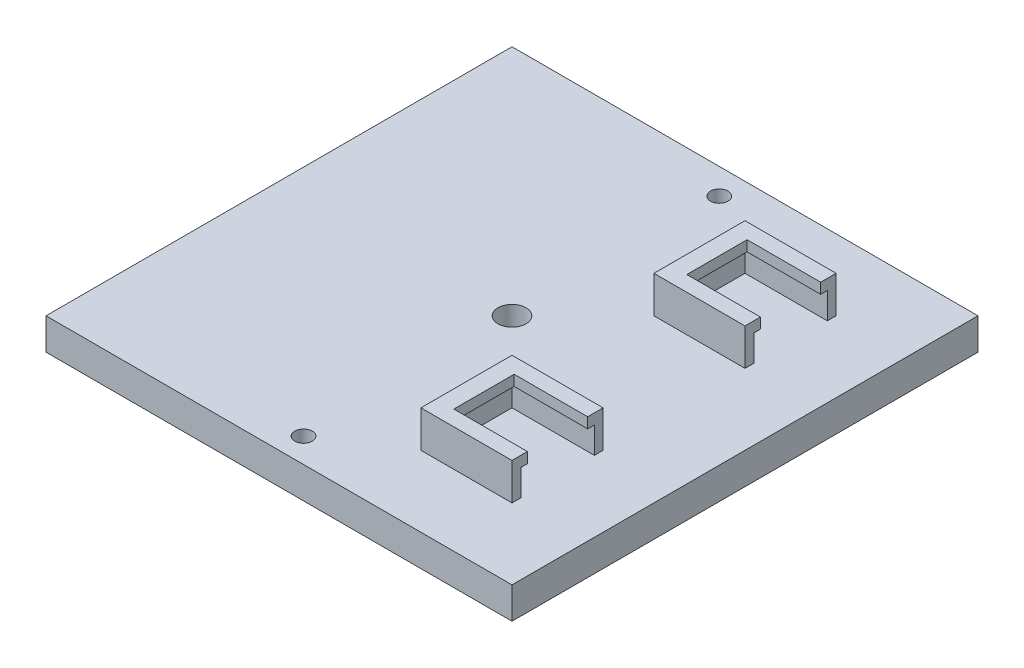
SolidWorks part; units mm, degrees
ref_plane "Front Plane" through (0, 0, 0) normal (0, 0, 1) x (1, 0, 0)
ref_plane "Top Plane" through (0, 0, 0) normal (0, 1, 0) x (1, 0, 0)
ref_plane "Right Plane" through (0, 0, 0) normal (1, 0, 0) x (0, 0, -1)
sketch "Sketch1" plane through (0, 0, 0) normal (0, 1, 0) x (1, 0, 0)
  line L1 (-66.5, -66.5) -> (66.5, -66.5)
  line L2 (-66.5, -66.5) -> (-66.5, 66.5)
  line L3 (-66.5, 66.5) -> (66.5, 66.5)
  line L4 (66.5, -66.5) -> (66.5, 66.5)
  line L5 (-66.5, -66.5) -> (66.5, 66.5) construction
  line L6 (-66.5, 66.5) -> (66.5, -66.5) construction
  point P0 (0, 0)
extrude "Boss-Extrude2" add sketch "Sketch1" along normal blind 136
sketch "Sketch2" plane through (0, 0, 66.5) normal (0, 0, 1) x (1, 0, 0)
  line L0 (66.5, 136) -> (66.5, 0) construction
  line L1 (-66.5, 136) -> (66.5, 136)
  line L2 (-66.5, 136) -> (-66.5, 127)
  line L3 (-66.5, 127) -> (66.5, 127)
  line L4 (66.5, 136) -> (66.5, 127)
  line L6 (-66.5, 0) -> (66.5, 0)
  line L7 (-66.5, 0) -> (-66.5, 9)
  line L8 (-66.5, 9) -> (66.5, 9)
  line L9 (66.5, 0) -> (66.5, 9)
  line L10 (-66.5, 127) -> (66.5, 127)
  line L11 (-66.5, 127) -> (-66.5, 9)
  line L12 (-66.5, 9) -> (66.5, 9)
  line L13 (66.5, 127) -> (66.5, 9)
  line M2 (66.5, 0) -> (66.5, 136)
  line M4 (-66.5, 136) -> (-66.5, 0)
extrude "Cut-Extrude1" cut sketch "Sketch2" against normal blind 136 contours L8 L3 M4 M2
sketch "Sketch4" plane through (0, 9, 0) normal (0, 1, 0) x (1, 0, 0)
  line L0 (0, 66.5) -> (0, -66.5) construction
  line L1 (-66.5, 66.5) -> (66.5, 66.5) construction
  line L2 (-66.5, -66.5) -> (66.5, -66.5) construction
  line L3 (0, -66.5) -> (33.25, -66.5) construction
  line L4 (33.25, -66.5) -> (33.25, 66.5) construction
  line L5 (0, 0) -> (66.5, 0) construction
  line L6 (66.5, 66.5) -> (66.5, -66.5) construction
  line L7 (66.5, 0) -> (66.5, 33.25) construction
  line L8 (66.5, 33.25) -> (0, 33.25) construction
  line L9 (0, 33.25) -> (0, -33.25) construction
  line L10 (0, -33.25) -> (66.5, -33.25) construction
  line L11 (43.75, 43.75) -> (22.75, 43.75)
  line L12 (43.75, -22.75) -> (22.75, -22.75)
  line L13 (43.75, -22.75) -> (43.75, -43.75)
  line L14 (43.75, -43.75) -> (22.75, -43.75)
  line L15 (22.75, -22.75) -> (22.75, -43.75)
  line L16 (43.75, -22.75) -> (22.75, -43.75) construction
  line L17 (43.75, -43.75) -> (22.75, -22.75) construction
  line L18 (46.25, -20.25) -> (20.25, -20.25)
  line L19 (46.25, -20.25) -> (46.25, -46.25)
  line L20 (46.25, -46.25) -> (20.25, -46.25)
  line L21 (20.25, -20.25) -> (20.25, -46.25)
  line L22 (46.25, -20.25) -> (20.25, -46.25) construction
  line L23 (46.25, -46.25) -> (20.25, -20.25) construction
  line L24 (22.75, 22.75) -> (22.75, 43.75)
  line L25 (43.75, 22.75) -> (22.75, 22.75)
  line L26 (43.75, 22.75) -> (43.75, 43.75)
  line L27 (46.25, 46.25) -> (20.25, 46.25)
  line L28 (20.25, 20.25) -> (20.25, 46.25)
  line L29 (46.25, 20.25) -> (20.25, 20.25)
  line L30 (46.25, 20.25) -> (46.25, 46.25)
  line L31 (46.25, 46.25) -> (20.25, 20.25) construction
  line L32 (46.25, 20.25) -> (20.25, 46.25) construction
  line L34 (43.75, -43.75) -> (46.25, -43.75)
  line L35 (43.75, -43.75) -> (43.75, -22.75)
  line L36 (43.75, -22.75) -> (46.25, -22.75)
  line L37 (46.25, -43.75) -> (46.25, -22.75)
  line L38 (43.75, 22.75) -> (46.25, 22.75)
  line L39 (43.75, 22.75) -> (43.75, 43.75)
  line L40 (43.75, 43.75) -> (46.25, 43.75)
  line L41 (46.25, 22.75) -> (46.25, 43.75)
  point P18 (33.25, -33.25)
  point P23 (33.25, -33.25)
  point P36 (33.25, 33.25)
extrude "Boss-Extrude3" add sketch "Sketch4" along normal blind 10.5 contours L12 L36 L19 L18 L21 L20 L34 L14 L15 | L11 L40 L30 L27 L28 L29 L38 L25 L24
sketch "Sketch5" plane through (22.75, 0, 0) normal (1, 0, 0) x (0, 0, -1)
  line L0 (-22.75, 19.5) -> (-22.75, 9) construction
  line L1 (-43.75, 19.5) -> (-22.75, 19.5)
  line L2 (-43.75, 19.5) -> (-43.75, 16.5)
  line L3 (-43.75, 16.5) -> (-22.75, 16.5)
  line L4 (-22.75, 19.5) -> (-22.75, 16.5)
  line L5 (43.75, 19.5) -> (43.75, 9) construction
  line L6 (22.75, 19.5) -> (43.75, 19.5)
  line L7 (22.75, 19.5) -> (22.75, 16.5)
  line L8 (22.75, 16.5) -> (43.75, 16.5)
  line L9 (43.75, 19.5) -> (43.75, 16.5)
extrude "Boss-Extrude4" add sketch "Sketch5" along normal up to surface (23.5 mm away) up to face at (46.25, 14.25, 45)
sketch "Sketch6" plane through (0, 19.5, 0) normal (0, 1, 0) x (1, 0, 0)
  line L0 (46.25, -46.25) -> (46.25, -20.25) construction
  line L1 (46.25, 20.25) -> (46.25, 46.25) construction
  line L2 (67.25, -41.85) -> (25.25, -41.85)
  line L3 (67.25, -41.85) -> (67.25, -24.65)
  line L4 (67.25, -24.65) -> (25.25, -24.65)
  line L5 (25.25, -41.85) -> (25.25, -24.65)
  line L6 (67.25, -41.85) -> (25.25, -24.65) construction
  line L7 (67.25, -24.65) -> (25.25, -41.85) construction
  line L9 (67.25, 24.65) -> (25.25, 24.65)
  line L10 (67.25, 24.65) -> (67.25, 41.85)
  line L11 (67.25, 41.85) -> (25.25, 41.85)
  line L12 (25.25, 24.65) -> (25.25, 41.85)
  line L13 (67.25, 24.65) -> (25.25, 41.85) construction
  line L14 (67.25, 41.85) -> (25.25, 24.65) construction
  point P4 (46.25, -33.25)
  point P13 (46.25, 33.25)
extrude "Cut-Extrude2" cut sketch "Sketch6" against normal up to surface (3 mm away) up to face at (34.5, 16.5, -33.25)
sketch "Sketch7" plane through (0, 127, 0) normal (0, -1, 0) x (1, 0, 0)
  line L0 (0, 66.5) -> (0, -66.5) construction
  line L1 (-66.5, 66.5) -> (66.5, 66.5) construction
  line L2 (-66.5, -66.5) -> (66.5, -66.5) construction
  line L3 (0, -66.5) -> (-33.25, -66.5) construction
  line L4 (-33.25, -66.5) -> (-33.25, 66.5) construction
  line L5 (-33.25, 66.5) -> (-66.5, 66.5) construction
  line L6 (-66.5, 66.5) -> (-66.5, 0) construction
  line L8 (-66.5, 0) -> (0, 0) construction
  line L9 (0, 0) -> (0, -33.25) construction
  line L10 (0, -33.25) -> (-66.5, -33.25) construction
  line L11 (-66.5, -66.5) -> (-66.5, 66.5) construction
  line L12 (-66.5, -33.25) -> (-66.5, 33.25) construction
  line L13 (-66.5, 33.25) -> (0, 33.25) construction
  line L14 (-22.75, -22.75) -> (-43.75, -22.75)
  line L15 (-22.75, 43.75) -> (-43.75, 43.75)
  line L16 (-22.75, 43.75) -> (-22.75, 22.75)
  line L17 (-22.75, 22.75) -> (-43.75, 22.75)
  line L18 (-43.75, 43.75) -> (-43.75, 22.75)
  line L19 (-22.75, 43.75) -> (-43.75, 22.75) construction
  line L20 (-22.75, 22.75) -> (-43.75, 43.75) construction
  line L21 (-20.25, 46.25) -> (-46.25, 46.25)
  line L22 (-20.25, 46.25) -> (-20.25, 20.25)
  line L23 (-20.25, 20.25) -> (-46.25, 20.25)
  line L24 (-46.25, 46.25) -> (-46.25, 20.25)
  line L25 (-20.25, 46.25) -> (-46.25, 20.25) construction
  line L26 (-20.25, 20.25) -> (-46.25, 46.25) construction
  line L27 (-43.75, -43.75) -> (-43.75, -22.75)
  line L28 (-22.75, -43.75) -> (-43.75, -43.75)
  line L29 (-22.75, -43.75) -> (-22.75, -22.75)
  line L30 (-20.25, -20.25) -> (-46.25, -20.25)
  line L31 (-46.25, -46.25) -> (-46.25, -20.25)
  line L32 (-20.25, -46.25) -> (-46.25, -46.25)
  line L33 (-20.25, -46.25) -> (-20.25, -20.25)
  line L34 (-20.25, -20.25) -> (-46.25, -46.25) construction
  line L35 (-20.25, -46.25) -> (-46.25, -20.25) construction
  line L36 (-43.75, -22.75) -> (-46.25, -22.75)
  line L37 (-43.75, 43.75) -> (-46.25, 43.75)
  line L38 (-43.75, 43.75) -> (-43.75, 22.75)
  line L39 (-43.75, 22.75) -> (-46.25, 22.75)
  line L40 (-46.25, 43.75) -> (-46.25, 22.75)
  line L41 (-46.25, -43.75) -> (-46.25, -22.75)
  line L42 (-43.75, -43.75) -> (-46.25, -43.75)
  line L43 (-43.75, -43.75) -> (-43.75, -22.75)
  point P17 (-33.25, 33.25)
  point P24 (-33.25, 33.25)
  point P37 (-33.25, -33.25)
extrude "Boss-Extrude5" add sketch "Sketch7" along normal blind 10.5 contours L17 L39 L24 L23 L22 L21 L37 L15 L16 | L28 L42 L31 L32 L33 L30 L36 L14 L29
sketch "Sketch8" plane through (-22.75, 0, 0) normal (-1, 0, 0) x (0, 0, 1)
  line L0 (22.75, 116.5) -> (22.75, 127) construction
  line L1 (43.75, 116.5) -> (22.75, 116.5)
  line L2 (43.75, 116.5) -> (43.75, 119.5)
  line L3 (43.75, 119.5) -> (22.75, 119.5)
  line L4 (22.75, 116.5) -> (22.75, 119.5)
  line L5 (-22.75, 116.5) -> (-22.75, 127) construction
  line L6 (-43.75, 116.5) -> (-22.75, 116.5)
  line L7 (-43.75, 116.5) -> (-43.75, 119.5)
  line L8 (-43.75, 119.5) -> (-22.75, 119.5)
  line L9 (-22.75, 116.5) -> (-22.75, 119.5)
extrude "Boss-Extrude6" add sketch "Sketch8" along normal up to surface (23.5 mm away) up to face at (-46.25, 121.75, 45)
sketch "Sketch9" plane through (0, 116.5, 0) normal (0, -1, 0) x (1, 0, 0)
  line L0 (-46.25, 46.25) -> (-46.25, 20.25) construction
  line L1 (-46.25, 20.25) -> (-46.25, -20.25) construction
  line L2 (-46.25, -20.25) -> (-46.25, -46.25) construction
  line L4 (-67.25, 41.85) -> (-25.25, 41.85)
  line L5 (-67.25, 41.85) -> (-67.25, 24.65)
  line L6 (-67.25, 24.65) -> (-25.25, 24.65)
  line L7 (-25.25, 41.85) -> (-25.25, 24.65)
  line L8 (-67.25, 41.85) -> (-25.25, 24.65) construction
  line L9 (-67.25, 24.65) -> (-25.25, 41.85) construction
  line L10 (-67.25, -24.65) -> (-25.25, -24.65)
  line L11 (-67.25, -24.65) -> (-67.25, -41.85)
  line L12 (-67.25, -41.85) -> (-25.25, -41.85)
  line L13 (-25.25, -24.65) -> (-25.25, -41.85)
  line L14 (-67.25, -24.65) -> (-25.25, -41.85) construction
  line L15 (-67.25, -41.85) -> (-25.25, -24.65) construction
  point P4 (-46.25, 33.25)
  point P13 (-46.25, -33.25)
extrude "Cut-Extrude3" cut sketch "Sketch9" against normal up to surface (3 mm away) up to face at (-34.5, 119.5, 33.25)
sketch "Sketch10" plane through (0, 0, 0) normal (0, -1, 0) x (1, 0, 0)
  line L0 (-66.5, -66.5) -> (66.5, -66.5) construction
  line L1 (66.5, -66.5) -> (0, -66.5) construction
  line L2 (0, -66.5) -> (0, 66.5) construction
  line L3 (-66.5, 66.5) -> (66.5, 66.5) construction
  line L5 (-9.6307, -66.5) -> (9.6307, -66.5)
  line L6 (-9.6307, -66.5) -> (-9.6307, 66.5)
  line L7 (-9.6307, 66.5) -> (9.6307, 66.5)
  line L8 (9.6307, -66.5) -> (9.6307, 66.5)
  line L9 (-9.6307, -66.5) -> (9.6307, 66.5) construction
  line L10 (-9.6307, 66.5) -> (9.6307, -66.5) construction
  point P4 (0, 0)
extrude "Boss-Extrude7" add sketch "Sketch10" along normal blind 5
sketch "Sketch11" plane through (0, 136, 0) normal (0, 1, 0) x (1, 0, 0)
  line L0 (-66.5, -66.5) -> (66.5, -66.5) construction
  line L1 (66.5, -66.5) -> (0, -66.5) construction
  line L2 (0, -66.5) -> (0, 66.5) construction
  line L3 (66.5, 66.5) -> (-66.5, 66.5) construction
  line L4 (0, 66.5) -> (0, 0) construction
  line L6 (-9.2186, -66.5) -> (9.2186, -66.5)
  line L7 (-9.2186, -66.5) -> (-9.2186, 66.5)
  line L8 (-9.2186, 66.5) -> (9.2186, 66.5)
  line L9 (9.2186, -66.5) -> (9.2186, 66.5)
  line L10 (-9.2186, -66.5) -> (9.2186, 66.5) construction
  line L11 (-9.2186, 66.5) -> (9.2186, -66.5) construction
extrude "Boss-Extrude8" add sketch "Sketch11" along normal blind 5
sketch "Sketch12" plane through (0, 0, -66.5) normal (0, 0, -1) x (-1, 0, 0)
  line L1 (-9.6307, -5) -> (9.2186, -5)
  line L2 (-9.6307, -5) -> (-9.6307, 141)
  line L3 (-9.6307, 141) -> (9.2186, 141)
  line L4 (9.2186, -5) -> (9.2186, 141)
extrude "Boss-Extrude9" add sketch "Sketch12" along normal blind 12
sketch "Sketch14" plane through (0, 0, 66.5) normal (0, 0, 1) x (1, 0, 0)
  line L1 (-9.2186, 141) -> (9.6307, 141)
  line L2 (-9.2186, 141) -> (-9.2186, -5)
  line L3 (-9.2186, -5) -> (9.6307, -5)
  line L4 (9.6307, 141) -> (9.6307, -5)
extrude "Boss-Extrude10" add sketch "Sketch14" along normal blind 12
sketch "Sketch17" plane through (0, 0, 78.5) normal (0, 0, 1) x (1, 0, 0)
  line L0 (-9.2186, 141) -> (9.6307, -5) construction
  line L1 (9.6307, -5) -> (0.2061, 68) construction
  circle A0 centre (0.2061, 68) radius 1
extrude "Cut-Extrude4" cut sketch "Sketch17" against normal through all
sketch "Sketch20" plane through (-9.2186, 0, 0) normal (-1, 0, 0) x (0, 0, 1)
  line L0 (-78.5, 141) -> (78.5, 141) construction
  line L1 (-66.5, 136) -> (66.7446, 136)
  line L2 (-66.5, 136) -> (-66.5, 141)
  line L3 (-66.5, 141) -> (66.7446, 141)
  line L4 (66.7446, 136) -> (66.7446, 141)
extrude "Cut-Extrude10" cut sketch "Sketch20" against normal blind 19
sketch "Sketch21" plane through (-9.2186, 0, 0) normal (-1, 0, 0) x (0, 0, 1)
  line L0 (78.5, 141) -> (78.5, -5) construction
  line L1 (-78.5, 141) -> (78.5, 141)
  line L2 (-78.5, 141) -> (-78.5, 20.3342)
  line L3 (-78.5, 20.3342) -> (78.5, 20.3342)
  line L4 (78.5, 141) -> (78.5, 20.3342)
extrude "Cut-Extrude11" cut sketch "Sketch21" against normal blind 118
sketch "Sketch22" plane through (-66.5, 0, 0) normal (-1, 0, 0) x (0, 0, 1)
  line L1 (-72.3811, 141.6622) -> (113.7932, 141.6622)
  line L2 (-72.3811, 141.6622) -> (-72.3811, 99.4099)
  line L3 (-72.3811, 99.4099) -> (113.7932, 99.4099)
  line L4 (113.7932, 141.6622) -> (113.7932, 99.4099)
extrude "Cut-Extrude12" cut sketch "Sketch22" against normal blind 118
sketch "Sketch23" plane through (-9.2186, 0, 0) normal (-1, 0, 0) x (0, 0, 1)
  line L1 (-78.5, 20.3342) -> (-66.5, 20.3342)
  line L2 (-78.5, 20.3342) -> (-78.5, -5)
  line L3 (-78.5, -5) -> (-66.5, -5)
  line L4 (-66.5, 20.3342) -> (-66.5, -5)
extrude "Cut-Extrude13" cut sketch "Sketch23" against normal blind 118
sketch "Sketch24" plane through (-9.2186, 0, 0) normal (-1, 0, 0) x (0, 0, 1)
  line L1 (66.5, 20.3342) -> (78.5, 20.3342)
  line L2 (66.5, 20.3342) -> (66.5, -5)
  line L3 (66.5, -5) -> (78.5, -5)
  line L4 (78.5, 20.3342) -> (78.5, -5)
extrude "Cut-Extrude14" cut sketch "Sketch24" against normal blind 118
sketch "Sketch31" plane through (0, -5, 0) normal (0, -1, 0) x (1, 0, 0)
  circle A0 centre (0, 59.4995) radius 2.5
extrude "Cut-Extrude21" cut sketch "Sketch31" against normal blind 118
sketch "Sketch32" plane through (0, -5, 0) normal (0, -1, 0) x (1, 0, 0)
  line L0 (-66.5, -66.5) -> (66.5, -66.5) construction
  circle A0 centre (0, -59.1598) radius 2.5
  dimension "D1" = 7.3402
extrude "Cut-Extrude22" cut sketch "Sketch32" against normal blind 118
sketch "Sketch33" plane through (-9.6307, 0, 0) normal (-1, 0, 0) x (0, 0, 1)
  line L1 (-66.5, -5) -> (66.5, -5)
  line L2 (-66.5, -5) -> (-66.5, 0)
  line L3 (-66.5, 0) -> (66.5, 0)
  line L4 (66.5, -5) -> (66.5, 0)
extrude "Cut-Extrude24" cut sketch "Sketch33" against normal blind 118
sketch "Sketch34" plane through (0, 9, 0) normal (0, 1, 0) x (1, 0, 0)
  circle A0 centre (0, 0) radius 2.5
extrude "Cut-Extrude25" cut sketch "Sketch34" against normal blind 118
sketch "Sketch35" plane through (0, 9, 0) normal (0, 1, 0) x (1, 0, 0)
  circle A0 centre (0, 0) radius 4
extrude "Cut-Extrude26" cut sketch "Sketch35" against normal blind 10
